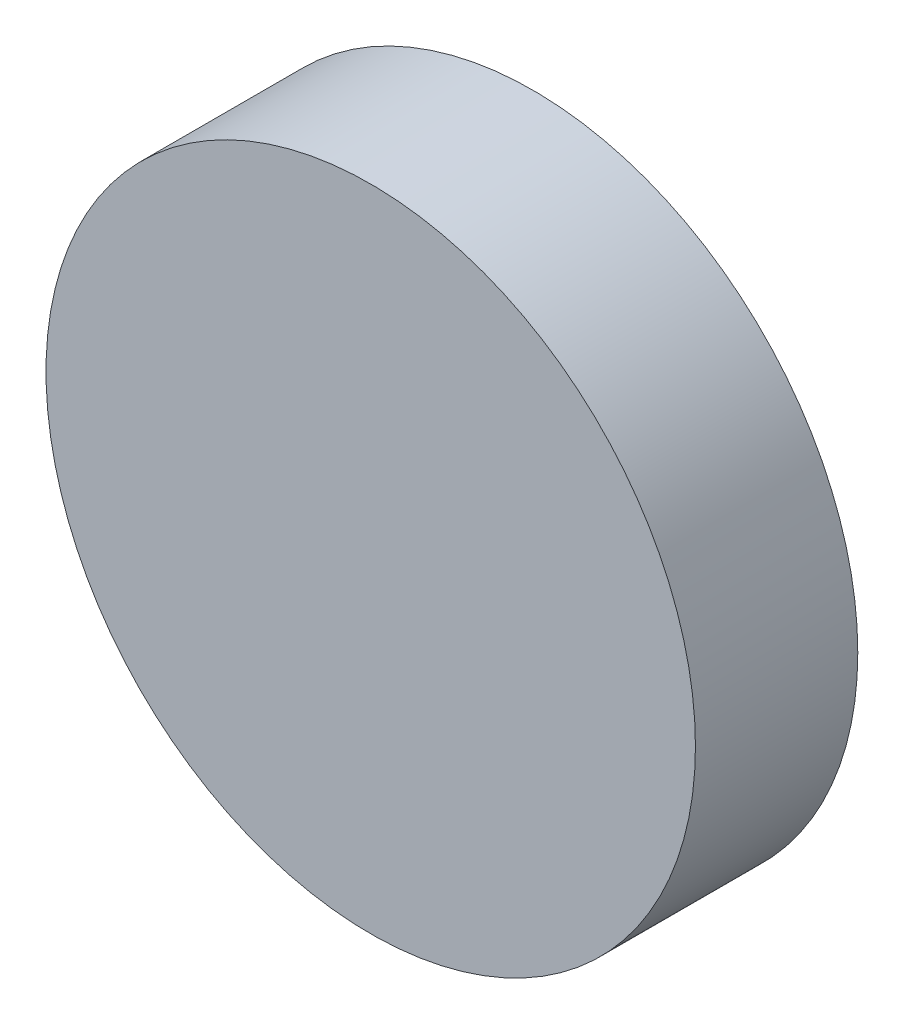
SolidWorks part; units mm, degrees
ref_plane "Front Plane" through (0, 0, 0) normal (0, 0, 1) x (1, 0, 0)
ref_plane "Top Plane" through (0, 0, 0) normal (0, 1, 0) x (1, 0, 0)
ref_plane "Right Plane" through (0, 0, 0) normal (1, 0, 0) x (0, 0, -1)
sketch "Sketch1" plane through (0, 0, 0) normal (0, 0, 1) x (1, 0, 0)
  circle A0 centre (-30.291, 15.9182) radius 25.4
  dimension "D1" = 50.8
extrude "Boss-Extrude1" add sketch "Sketch1" along normal blind 12.7 contours A0
